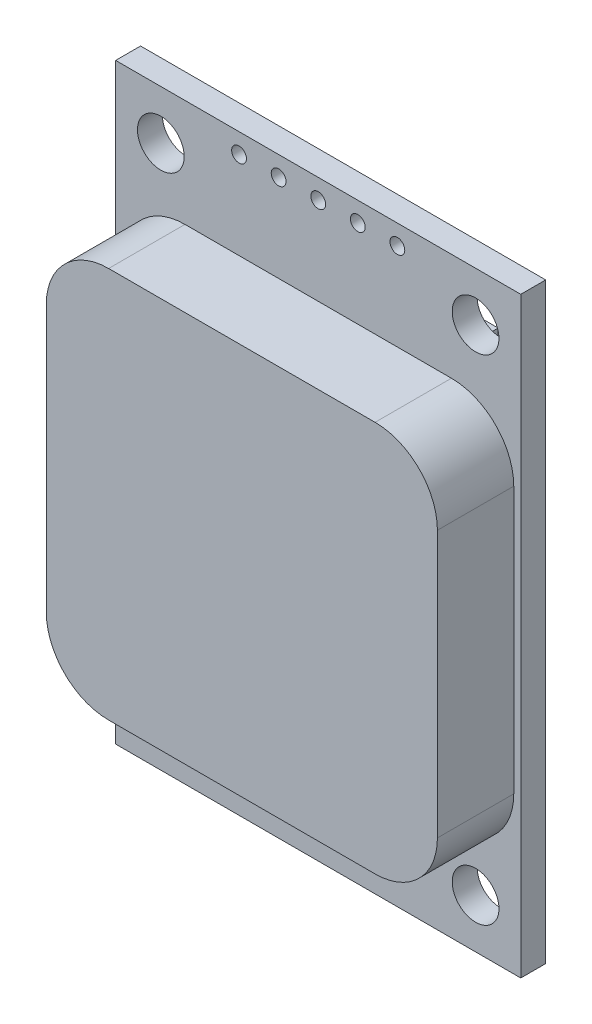
SolidWorks part; units mm, degrees
ref_plane "Front" through (0, 0, 0) normal (0, 0, 1) x (1, 0, 0)
ref_plane "Top" through (0, 0, 0) normal (0, 1, 0) x (1, 0, 0)
ref_plane "Right" through (0, 0, 0) normal (1, 0, 0) x (0, 0, -1)
sketch "草图1" plane through (0, 0, 0) normal (0, 0, 1) x (1, 0, 0)
  line L0 (-34.5801, 0) -> (41.2282, 0) construction
  line L1 (-13, 19) -> (13, 19)
  line L2 (-13, 19) -> (-13, -19)
  line L3 (-13, -19) -> (13, -19)
  line L4 (13, 19) -> (13, -19)
  line L5 (0, 28.4781) -> (0, -24.2391) construction
  dimension "D1" = 26
  dimension "D2" = 38
extrude "凸台-拉伸1" add sketch "草图1" against normal blind 1.6
sketch "草图2" plane through (0, 0, 0) normal (0, 0, 1) x (1, 0, 0)
  line L0 (-25.2887, 0) -> (25.4566, 0) construction
  line L1 (0, 25.3753) -> (0, -32.8404) construction
  circle A0 centre (-10.1, 15.85) radius 1.5
  circle A1 centre (10.1, 15.85) radius 1.5
  circle A2 centre (10.1, -15.85) radius 1.5
  circle A3 centre (-10.1, -15.85) radius 1.5
  dimension "D1" = 3
  dimension "D2" = 3
  dimension "D3" = 3
  dimension "D4" = 3
  dimension "D5" = 20.2
  dimension "D6" = 31.7
extrude "切除-拉伸1" cut sketch "草图2" against normal up to next
sketch "草图3" plane through (0, 0, 0) normal (0, 0, 1) x (1, 0, 0)
  line L0 (0, 25.4698) -> (0, -25.6052) construction
  line L1 (-12.55, 12.11) -> (12.55, 12.11)
  line L2 (-12.55, 12.11) -> (-12.55, -12.99)
  line L3 (-12.55, -12.99) -> (12.55, -12.99)
  line L4 (12.55, 12.11) -> (12.55, -12.99)
  line L5 (13, 19) -> (-13, 19) construction
  dimension "D1" = 25.1
  dimension "D2" = 25.1
  dimension "D3" = 6.89
extrude "凸台-拉伸2" add sketch "草图3" along normal blind 4.9
fillet "圆角1" radius 4 4 edges at (-12.55, 12.11, 2.45) (-12.55, -12.99, 2.45) (12.55, -12.99, 2.45) (12.55, 12.11, 2.45)
sketch "草图6" plane through (0, 0, -1.6) normal (0, 0, -1) x (-1, 0, 0)
  line L0 (0, 25.5714) -> (0, -24.1709) construction
  line L1 (-7.55, 12.4) -> (7.55, 12.4)
  line L2 (-7.55, 12.4) -> (-7.55, 0.7)
  line L3 (-7.55, 0.7) -> (7.55, 0.7)
  line L4 (7.55, 12.4) -> (7.55, 0.7)
  line L6 (-13, 19) -> (13, 19) construction
  dimension "D1" = 15.1
  dimension "D2" = 11.7
  dimension "D3" = 6.6
extrude "凸台-拉伸3" add sketch "草图6" along normal blind 2.4
sketch "草图7" plane through (0, 0, -1.6) normal (0, 0, -1) x (-1, 0, 0)
  line L0 (13, -19) -> (-13, -19) construction
  line L1 (-3.95, -13.3) -> (3.95, -13.3)
  line L2 (-3.95, -13.3) -> (-3.95, -19)
  line L3 (-3.95, -19) -> (3.95, -19)
  line L4 (3.95, -13.3) -> (3.95, -19)
  line L5 (0, 25.5798) -> (0, -28.4071) construction
  dimension "D1" = 5.7
  dimension "D2" = 7.9
extrude "凸台-拉伸4" add sketch "草图7" along normal blind 2.8
sketch "草图8" plane through (0, 0, -1.6) normal (0, 0, -1) x (-1, 0, 0)
  line L0 (0, 25.5734) -> (0, -32.6909) construction
  line L1 (-13, 19) -> (13, 19) construction
  circle A0 centre (0, 17.73) radius 0.475
  dimension "D1" = 0.95
  dimension "D2" = 1.27
extrude "切除-拉伸2" cut sketch "草图8" against normal up to next
pattern_linear "阵列(线性)1" count 3 spacing 2.54 along (-1, 0, 0) count 3 spacing 2.54 along (1, 0, 0) of "切除-拉伸2"
ref_plane "基准面1" through (0, 0, 0) normal (0, 1, 0) x (1, 0, 0)
ref_plane "基准面2" through (0, 0, 0) normal (-1, 0, 0) x (0, -1, 0)
